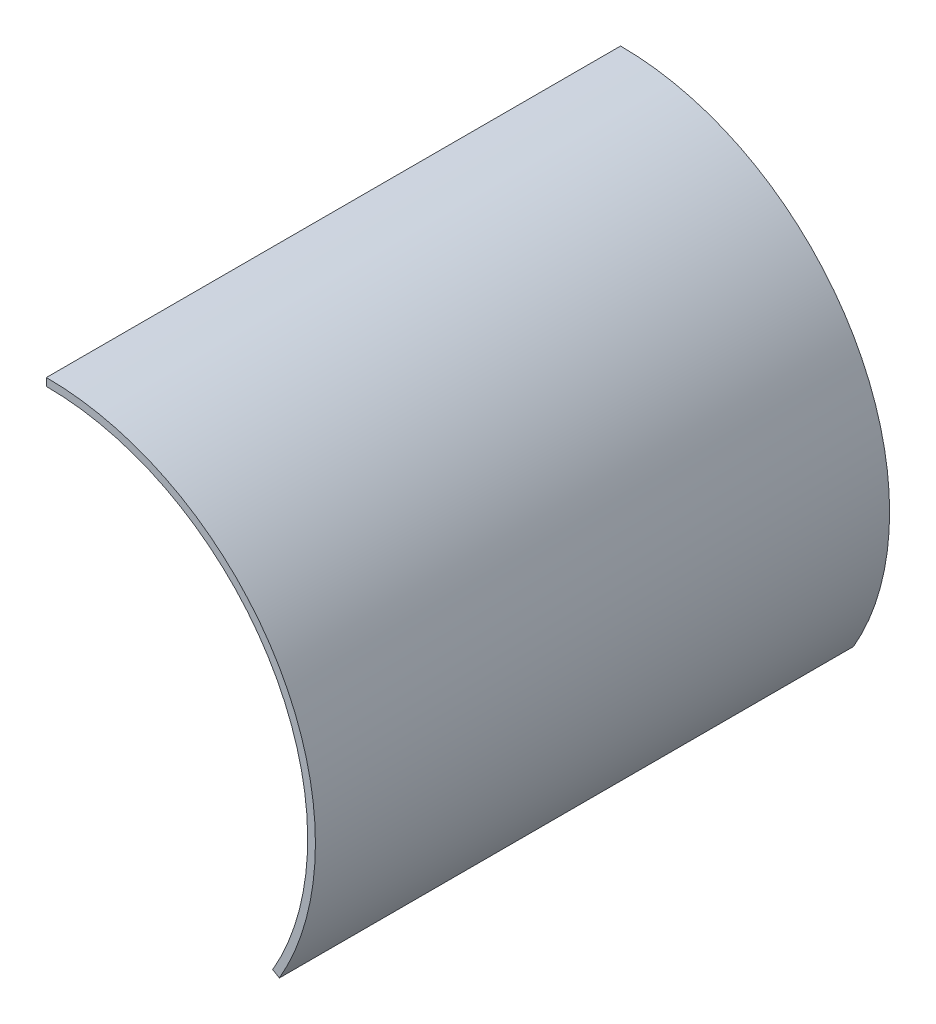
SolidWorks part; units mm, degrees
ref_plane "Front" through (0, 0, 0) normal (0, 0, 1) x (1, 0, 0)
ref_plane "Top" through (0, 0, 0) normal (0, 1, 0) x (1, 0, 0)
ref_plane "Right" through (0, 0, 0) normal (1, 0, 0) x (0, 0, -1)
sketch "Эскиз1" plane through (0, 0, 0) normal (1, 0, 0) x (0, 0, -1)
  line L0 (0, 41.7) -> (0, 40.5)
  line L1 (0, 40.5) -> (89, 40.5)
  line L2 (89, 40.5) -> (89, 41.7)
  line L3 (89, 41.7) -> (0, 41.7)
  line L4 (0, 0) -> (40.5832, 0) construction
  dimension "D1" = 1.2
  dimension "D2" = 40.5
  dimension "D3" = 89
revolve "Повернуть1" add sketch "Эскиз1" angle 120 about L4
